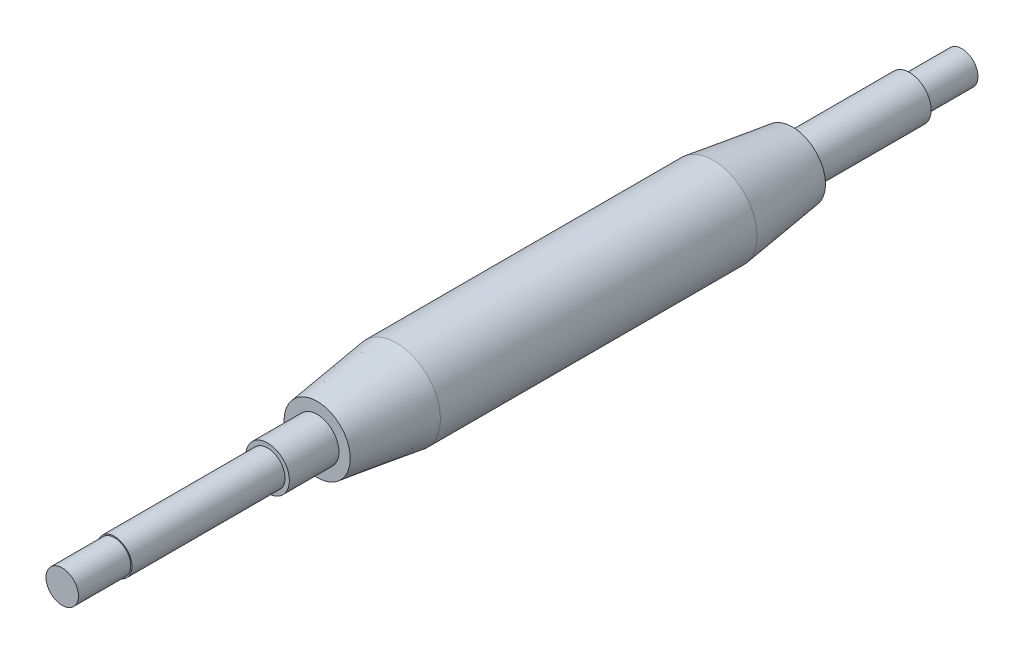
SolidWorks part; units mm, degrees
ref_plane "Plan1" through (0, 0, 0) normal (0, 0, 1) x (1, 0, 0)
ref_plane "Plan2" through (0, 0, 0) normal (0, 1, 0) x (1, 0, 0)
ref_plane "Plan3" through (0, 0, 0) normal (1, 0, 0) x (0, 0, -1)
sketch "Esquisse1" plane through (0, 0, 0) normal (1, 0, 0) x (0, 0, -1)
  line L0 (-59.9414, 0) -> (137.541, 0) construction
  line L1 (27.8, 3.16) -> (27.8, 3.95)
  line L2 (0, 3.16) -> (27.8, 3.16)
  line L3 (0, 2.95) -> (-9.5, 2.95)
  line L4 (-9.5, 2.95) -> (-9.5, 0)
  line L7 (0, 2.95) -> (0, 3.16)
  line L8 (27.8, 3.95) -> (36.8, 3.95)
  line L9 (36.8, 3.95) -> (36.8, 6)
  line L10 (36.8, 6) -> (51.2, 7.975)
  line L11 (51.2, 7.975) -> (108.7, 7.975)
  line L12 (108.7, 7.975) -> (123.1, 6)
  line L13 (123.1, 6) -> (123.1, 3.95)
  line L14 (123.1, 3.95) -> (144.35, 3.95)
  line L15 (144.35, 3.95) -> (144.35, 2.95)
  line L16 (144.35, 2.95) -> (153.85, 2.95)
  line L17 (153.85, 2.95) -> (153.85, 0)
  line L18 (153.85, 0) -> (-9.5, 0)
  dimension "D1" = 5.9
  dimension "D2" = 9.5
  dimension "D3" = 6.32
  dimension "D6" = 7.9
  dimension "D7" = 9
  dimension "D8" = 27.8
  dimension "D9" = 57.5
  dimension "D10" = 15.95
  dimension "D11" = 14.4
  dimension "D12" = 12
  dimension "D13" = 14.4
  dimension "D14" = 21.25
  dimension "D15" = 9.5
revolve "Base-Révolution" add sketch "Esquisse1" angle 360 about L0
